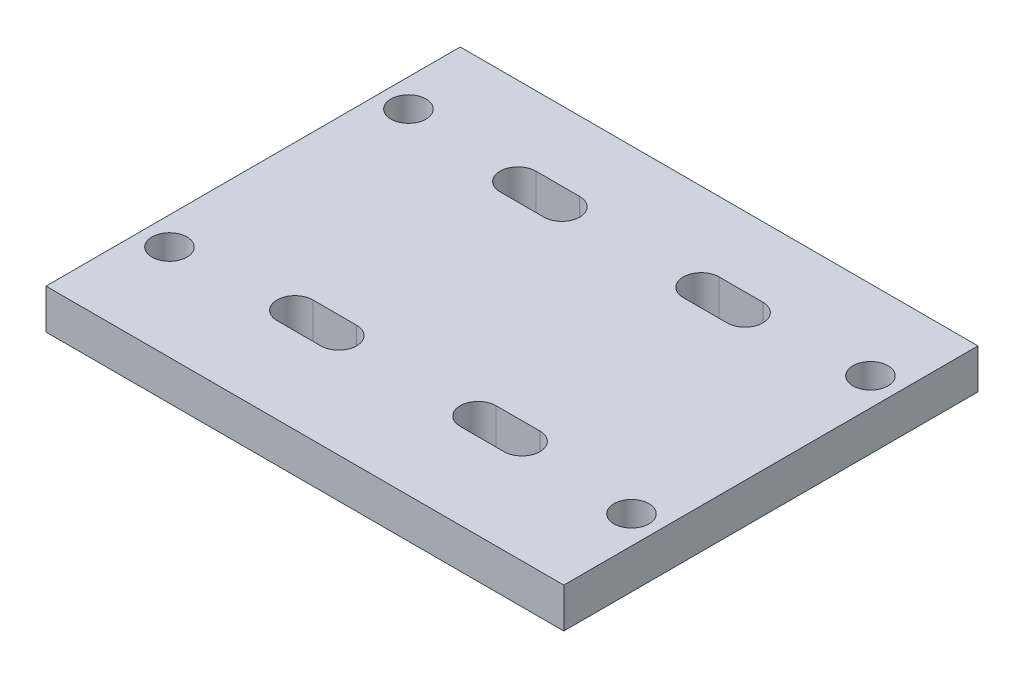
SolidWorks part; units mm, degrees
ref_plane "Ebene vorne" through (0, 0, 0) normal (0, 0, 1) x (1, 0, 0)
ref_plane "Ebene oben" through (0, 0, 0) normal (0, 1, 0) x (1, 0, 0)
ref_plane "Ebene rechts" through (0, 0, 0) normal (1, 0, 0) x (0, 0, -1)
sketch "Skizze1" plane through (0, 0, 0) normal (0, 1, 0) x (1, 0, 0)
  line L0 (-14.25, 15) -> (-8.75, 15) construction
  line L1 (-32.5, -26) -> (32.5, -26)
  line L2 (-32.5, -26) -> (-32.5, 26)
  line L3 (-32.5, 26) -> (32.5, 26)
  line L4 (32.5, -26) -> (32.5, 26)
  line L5 (-32.5, -26) -> (32.5, 26) construction
  line L6 (-32.5, 26) -> (32.5, -26) construction
  line L7 (-25, -26) -> (25, -26) construction
  line L8 (-25, -26) -> (-25, 26) construction
  line L9 (-25, 26) -> (25, 26) construction
  line L10 (25, -26) -> (25, 26) construction
  line L11 (-25, -26) -> (25, 26) construction
  line L12 (-25, 26) -> (25, -26) construction
  line L13 (-25, 26) -> (25, 26) construction
  line L14 (-25, 26) -> (-25, 23) construction
  line L15 (-25, 23) -> (25, 23) construction
  line L16 (25, 26) -> (25, 23) construction
  line L21 (-21, 23) -> (21, 23) construction
  line L22 (-21, 23) -> (-21, -43.5) construction
  line L23 (-21, -43.5) -> (21, -43.5) construction
  line L24 (21, 23) -> (21, -43.5) construction
  line L25 (-14.25, 17.25) -> (-8.75, 17.25)
  line L26 (-14.25, 12.75) -> (-8.75, 12.75)
  line L27 (8.75, 15) -> (14.25, 15) construction
  line L30 (8.75, 17.25) -> (14.25, 17.25)
  line L31 (8.75, 12.75) -> (14.25, 12.75)
  line L32 (-14.25, -13) -> (-8.75, -13) construction
  line L33 (-14.25, -10.75) -> (-8.75, -10.75)
  line L34 (-14.25, -15.25) -> (-8.75, -15.25)
  line L35 (8.75, -13) -> (14.25, -13) construction
  line L36 (8.75, -10.75) -> (14.25, -10.75)
  line L37 (8.75, -15.25) -> (14.25, -15.25)
  circle A0 centre (-29, 16) radius 2.2
  circle A1 centre (-29, -14) radius 2.2
  circle A2 centre (29, -14) radius 2.2
  circle A3 centre (29, 16) radius 2.2
  arc A4 (-14.25, 17.25) -> (-14.25, 12.75) centre (-14.25, 15) ccw
  arc A5 (-8.75, 12.75) -> (-8.75, 17.25) centre (-8.75, 15) ccw
  arc A8 (8.75, 17.25) -> (8.75, 12.75) centre (8.75, 15) ccw
  arc A9 (14.25, 12.75) -> (14.25, 17.25) centre (14.25, 15) ccw
  arc A10 (-14.25, -10.75) -> (-14.25, -15.25) centre (-14.25, -13) ccw
  arc A11 (-8.75, -15.25) -> (-8.75, -10.75) centre (-8.75, -13) ccw
  arc A12 (8.75, -10.75) -> (8.75, -15.25) centre (8.75, -13) ccw
  arc A13 (14.25, -15.25) -> (14.25, -10.75) centre (14.25, -13) ccw
  point P0 (0, 0)
  point P6 (0, 0)
  point P27 (-11.5, 15)
  point P32 (11.5, -13)
  point P36 (11.5, 15)
  point P41 (6.5, 15)
  point P42 (16.5, 15)
  point P45 (-11.5, -13)
  dimension "D9" = 12
  dimension "D23" = 4.4
  dimension "D1" = 52
  dimension "D2" = 65
  dimension "D3" = 50
  dimension "D4" = 52
  dimension "D5" = 3
  dimension "D6" = 66.5
  dimension "D7" = 42
  dimension "D8" = 4
  dimension "D10" = 4
  dimension "D11" = 10
  dimension "D12" = 4
  dimension "D13" = 4
  dimension "D14" = 12
  dimension "D15" = 10
  dimension "D16" = 28
  dimension "D17" = 11
  dimension "D18" = 13.5
  dimension "D19" = 10
  dimension "D20" = 13.5
  dimension "D21" = 11
  dimension "D22" = 4.5
extrude "Aufsatz-Linear austragen1" add sketch "Skizze1" along normal blind 5
